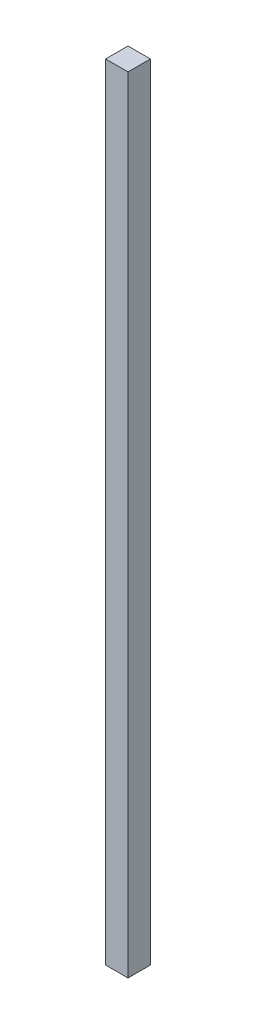
SolidWorks part; units mm, degrees
ref_plane "前视基准面" through (0, 0, 0) normal (0, 0, 1) x (1, 0, 0)
ref_plane "上视基准面" through (0, 0, 0) normal (0, 1, 0) x (1, 0, 0)
ref_plane "右视基准面" through (0, 0, 0) normal (1, 0, 0) x (0, 0, -1)
sketch "Sketch1" plane through (0, 0, 0) normal (0, 1, 0) x (1, 0, 0)
  line L1 (-10, 10) -> (10, 10)
  line L2 (-10, 10) -> (-10, -10)
  line L3 (-10, -10) -> (10, -10)
  line L4 (10, 10) -> (10, -10)
  line L5 (-10, 10) -> (10, -10) construction
  line L6 (-10, -10) -> (10, 10) construction
  point P0 (0, 0)
  dimension "D1" = 20
  dimension "D2" = 20
extrude "Boss-Extrude1" add sketch "Sketch1" along normal blind 700
